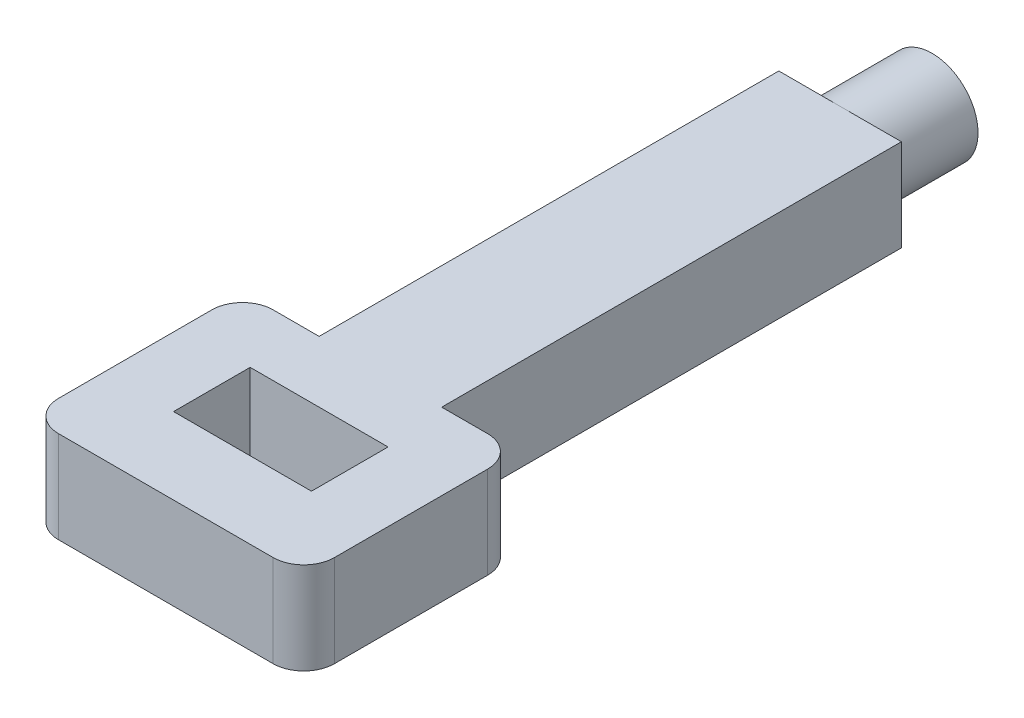
SolidWorks part; units mm, degrees
ref_plane "Front" through (0, 0, 0) normal (0, 0, 1) x (1, 0, 0)
ref_plane "Top" through (0, 0, 0) normal (0, 1, 0) x (1, 0, 0)
ref_plane "Right" through (0, 0, 0) normal (1, 0, 0) x (0, 0, -1)
sketch "Croquis1" plane through (0, 0, 0) normal (0, 1, 0) x (1, 0, 0)
  line L0 (-198.1915, 0) -> (9711.3819, 0) construction
  line L1 (0, -198.1915) -> (0, 9711.3819) construction
  line L2 (4.5, 0) -> (-4.5, 0)
  line L3 (-4.5, 0) -> (-4.5, 7)
  line L4 (-4.5, 7) -> (-2, 7)
  line L5 (-2, 7) -> (-2, 22)
  line L6 (-2, 22) -> (2, 22)
  line L7 (2, 7) -> (2, 22)
  line L8 (4.5, 7) -> (2, 7)
  line L9 (4.5, 0) -> (4.5, 7)
  line L11 (-2.25, 2.5) -> (2.25, 2.5)
  line L12 (-2.25, 2.5) -> (-2.25, 5)
  line L13 (-2.25, 5) -> (2.25, 5)
  line L14 (2.25, 2.5) -> (2.25, 5)
  line L15 (-2.25, 2.5) -> (2.25, 5) construction
  line L16 (-2.25, 5) -> (2.25, 2.5) construction
  point P4 (0, 22)
  point P11 (0, 3.75)
  point P15 (0, 0)
  dimension "D1" = 4.5
  dimension "D2" = 7
  dimension "D3" = 15
  dimension "D4" = 2.5
  dimension "D5" = 4.5
  dimension "D6" = 2.5
  dimension "D7" = 2.5
extrude "Saliente-Extruir1" add sketch "Croquis1" along normal blind 3
fillet "Redondeo1" radius 1 4 edges at (4.5, 1.5, -7) (-4.5, 1.5, -7) (4.5, 1.5, 0) (-4.5, 1.5, 0)
sketch "Croquis2" plane through (0, 0, -22) normal (0, 0, -1) x (-1, 0, 0)
  line L0 (-1000, 0) -> (49000, 0) construction
  line L1 (0, -1000) -> (0, 49000) construction
  line L2 (-1000.823, 1.5) -> (48999.177, 1.5) construction
  circle A0 centre (0, 1.5) radius 1.5
  dimension "D2" = 3
  dimension "D1" = 1.5
extrude "Saliente-Extruir2" add sketch "Croquis2" along normal blind 3
